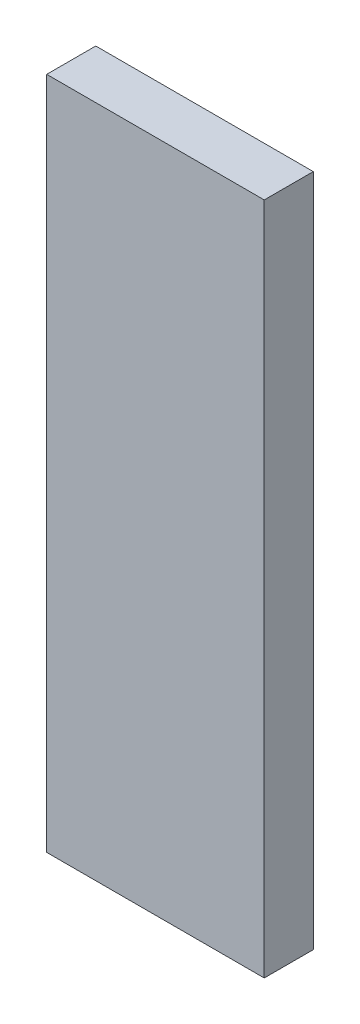
SolidWorks part; units mm, degrees
ref_plane "Спереди" through (0, 0, 0) normal (0, 0, 1) x (1, 0, 0)
ref_plane "Сверху" through (0, 0, 0) normal (0, 1, 0) x (1, 0, 0)
ref_plane "Справа" through (0, 0, 0) normal (1, 0, 0) x (0, 0, -1)
sketch "Эскиз1" plane through (0, 0, 0) normal (0, 0, 1) x (1, 0, 0)
  line L0 (0, 0) -> (66.5, 0) construction
  line L1 (66.5, -206) -> (66.5, 206)
  line L2 (66.5, 206) -> (-66.5, 206)
  line L3 (0, 206) -> (0, 0) construction
  line L4 (-66.5, -206) -> (-66.5, 206)
  line L5 (66.5, -206) -> (-66.5, -206)
  point P8 (-66.5, 0)
  dimension "D1" = 206
  dimension "D2" = 66.5
extrude "Бобышка-Вытянуть1" add sketch "Эскиз1" along normal blind 30
